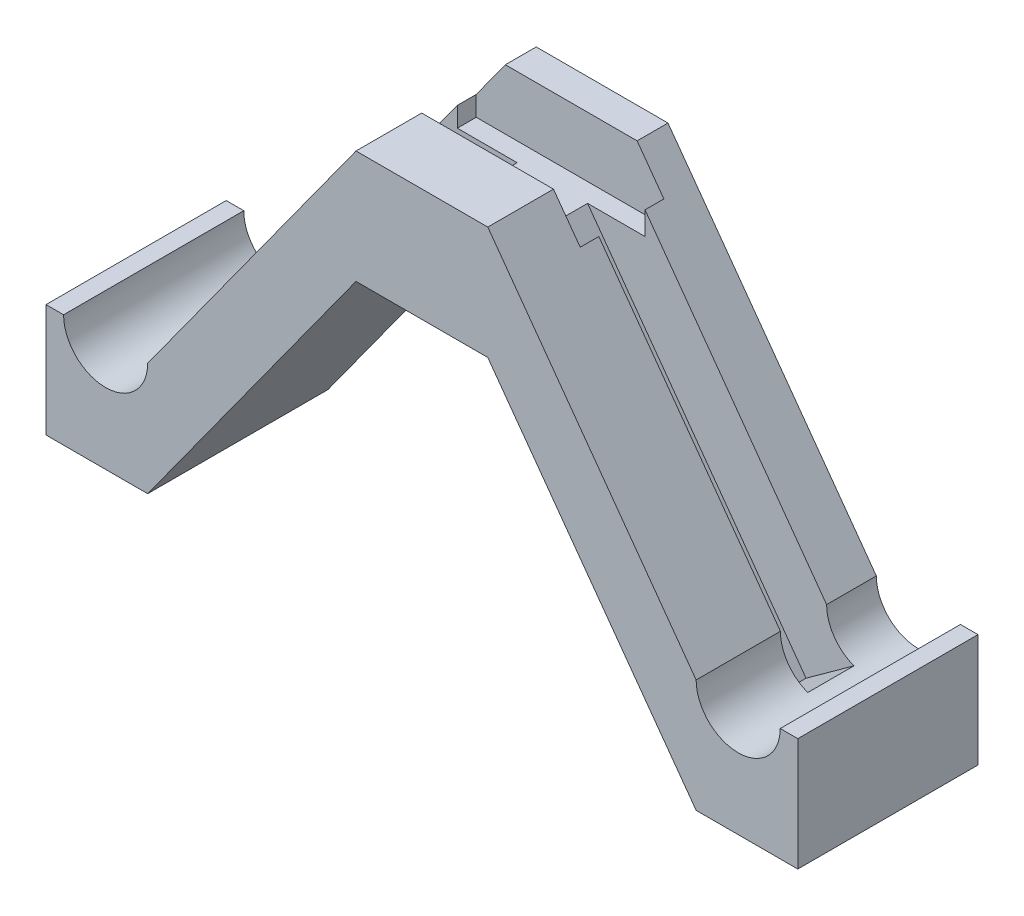
SolidWorks part; units mm, degrees
ref_plane "Front Plane" through (0, 0, 0) normal (0, 0, 1) x (1, 0, 0)
ref_plane "Top Plane" through (0, 0, 0) normal (0, 1, 0) x (1, 0, 0)
ref_plane "Right Plane" through (0, 0, 0) normal (1, 0, 0) x (0, 0, -1)
sketch "Sketch2" plane through (0, 0, 0) normal (0, 0, 1) x (1, 0, 0)
  line L0 (10.9701, 0) -> (-10.9701, 0)
  line L1 (-10.9701, 0) -> (-45.6567, -47.9552)
  line L2 (-45.6567, -47.9552) -> (-62.5821, -47.9552)
  line L3 (-62.5821, -47.9552) -> (-62.5821, -29.1493)
  line L4 (-62.5821, -29.1493) -> (-59.6567, -29.1493)
  line L5 (-45.6567, -29.1493) -> (-10.9701, 18.806)
  line L6 (-10.9701, 18.806) -> (10.9701, 18.806)
  line L7 (0, 18.806) -> (0, 0)
  line L8 (45.6567, -29.1493) -> (10.9701, 18.806)
  line L9 (62.5821, -29.1493) -> (59.6567, -29.1493)
  line L10 (62.5821, -47.9552) -> (62.5821, -29.1493)
  line L11 (45.6567, -47.9552) -> (62.5821, -47.9552)
  line L12 (10.9701, 0) -> (45.6567, -47.9552)
  arc A0 (-59.6567, -29.1493) -> (-45.6567, -29.1493) centre (-52.6567, -29.1493) ccw
  arc A1 (59.6567, -29.1493) -> (45.6567, -29.1493) centre (52.6567, -29.1493) cw
  dimension "D1" = 7
extrude "Boss-Extrude1" add sketch "Sketch2" along normal blind 30 contours A0 L4 L3 L2 L1 L0 L7 L6 L5 | L9 A1 L8 L6 L7 L0 L12 L11 L10
sketch "Sketch3" plane through (0, 18.806, 0) normal (0, 1, 0) x (1, 0, 0)
  line L1 (15.4209, -19.0654) -> (-15.8196, -19.0654)
  line L2 (15.4209, -19.0654) -> (15.4209, -5.1374)
  line L3 (15.4209, -5.1374) -> (-15.8196, -5.1374)
  line L4 (-15.8196, -19.0654) -> (-15.8196, -5.1374)
extrude "Cut-Extrude1" cut sketch "Sketch3" against normal blind 10
sketch "Sketch4" plane through (-16.1325, 11.6688, 0) normal (-0.8103, 0.5861, 0) x (0, 0, 1)
  line L1 (8.2776, 3.8298) -> (15.9675, 3.8298)
  line L2 (8.2776, 3.8298) -> (8.2776, -58.3546)
  line L3 (8.2776, -58.3546) -> (15.9675, -58.3546)
  line L4 (15.9675, 3.8298) -> (15.9675, -58.3546)
extrude "Cut-Extrude2" cut sketch "Sketch4" against normal blind 10
mirror "Mirror1" about plane through (0, 0, 0) normal (1, 0, 0) of "Cut-Extrude2"
